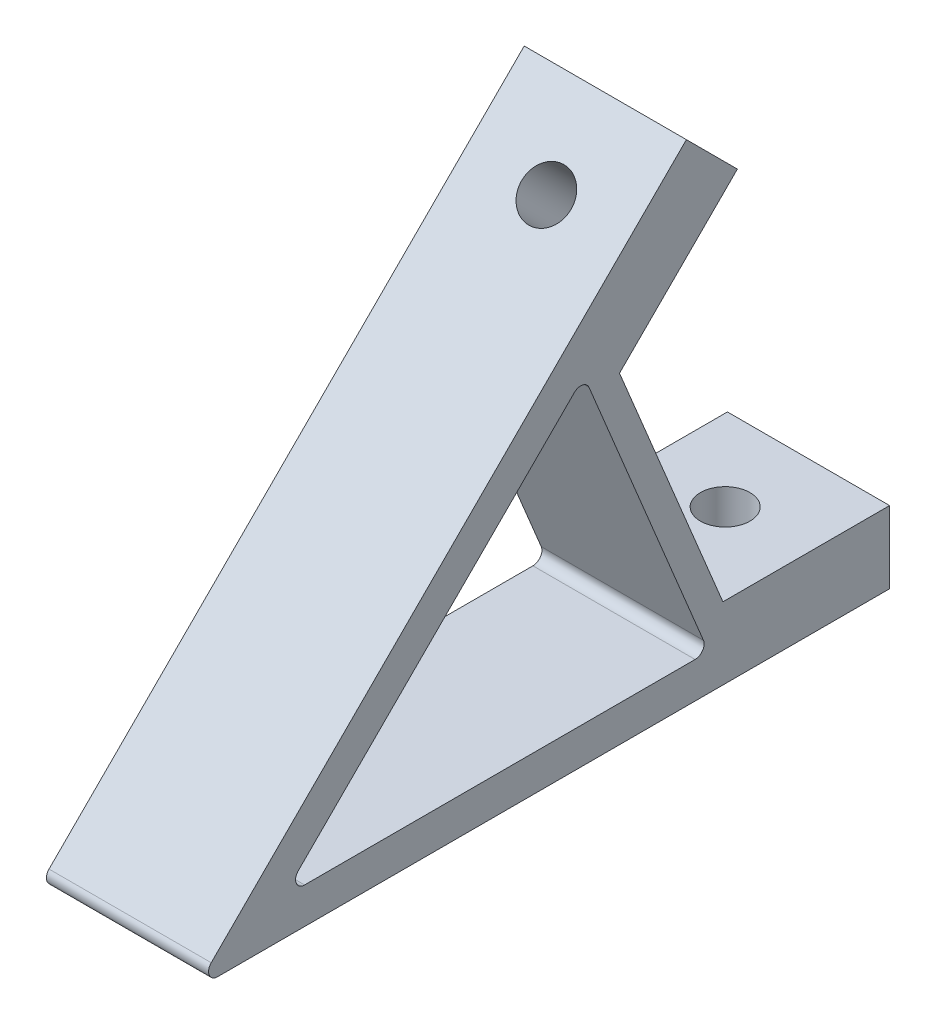
SolidWorks part; units mm, degrees
ref_plane "前视基准面" through (0, 0, 0) normal (0, 0, 1) x (1, 0, 0)
ref_plane "上视基准面" through (0, 0, 0) normal (0, 1, 0) x (1, 0, 0)
ref_plane "右视基准面" through (0, 0, 0) normal (1, 0, 0) x (0, 0, -1)
sketch "草图1" plane through (0, 0, 0) normal (1, 0, 0) x (0, 0, -1)
  line L0 (77, 0) -> (0, 0)
  line L1 (0, 0) -> (54.4472, 54.4472)
  line L2 (9.6569, 4) -> (56.9097, 4)
  line L3 (9.6569, 4) -> (43.0696, 37.4128)
  line L4 (43.0696, 37.4128) -> (56.9097, 4)
  line L7 (47.0226, 35.7089) -> (58.5, 8)
  line L11 (54.4472, 54.4472) -> (60.1041, 48.7904)
  line L12 (47.0226, 35.7089) -> (60.1041, 48.7904)
  line L13 (77, 0) -> (77, 8)
  line L14 (58.5, 8) -> (77, 8)
  dimension "D1" = 77
  dimension "D2" = 45
  dimension "D3" = 77
  dimension "D4" = 4
  dimension "D5" = 4
  dimension "D6" = 8
  dimension "D7" = 8
  dimension "D8" = 3
  dimension "D9" = 18.5
  dimension "D10" = 18.5
extrude "凸台-拉伸2" add sketch "草图1" along normal blind 18
fillet "圆角2" radius 1 4 edges at (9, 4, -56.9097) (9, 37.4128, -43.0696) (9, 4, -9.6569) (9, 0, 0)
sketch "草图2" plane through (0, 8, 0) normal (0, 1, 0) x (1, 0, 0)
  circle A0 centre (9, 67.75) radius 2.75
  point P8 (9, 67.75)
sketch "草图3" plane through (0, -5.6569, -5.6569) normal (0, -0.7071, -0.7071) x (1, 0, 0)
  circle A0 centre (9, -67.75) radius 2.75
  point P8 (9, -67.75)
extrude "切除-拉伸1" cut sketch "草图2" against normal up to next contours A0
extrude "切除-拉伸2" cut sketch "草图3" against normal up to next contours A0
